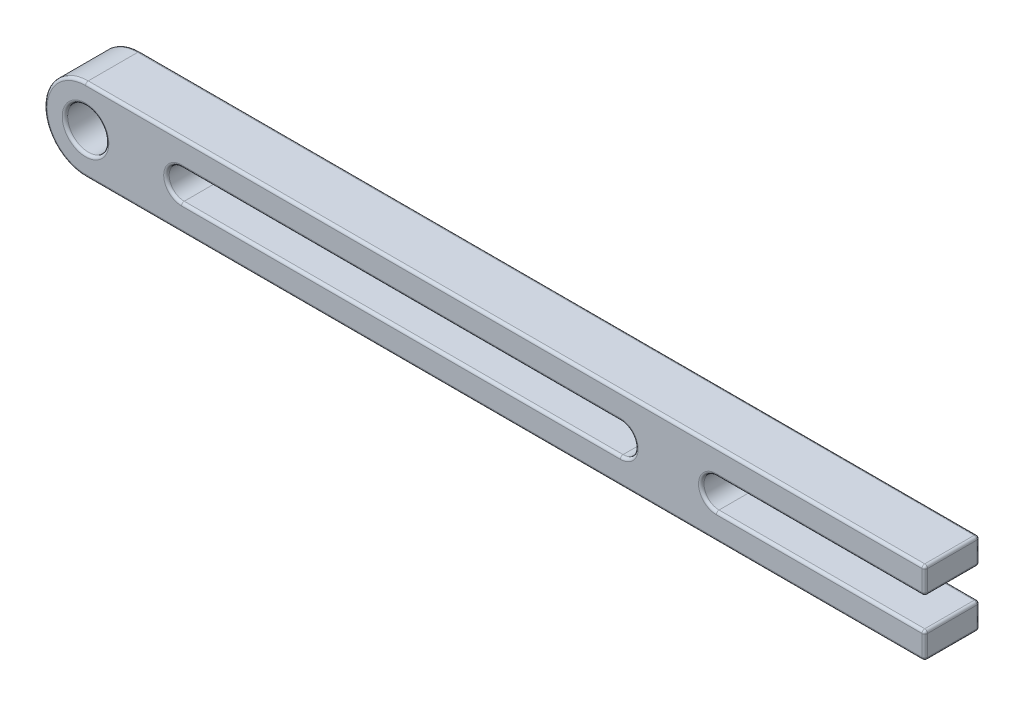
SolidWorks part; units mm, degrees
ref_plane "Front Plane" through (0, 0, 0) normal (0, 0, 1) x (1, 0, 0)
ref_plane "Top Plane" through (0, 0, 0) normal (0, 1, 0) x (1, 0, 0)
ref_plane "Right Plane" through (0, 0, 0) normal (1, 0, 0) x (0, 0, -1)
sketch "Sketch1" plane through (0, 0, 0) normal (0, 0, 1) x (1, 0, 0)
  line L0 (0, -1000) -> (0, 49000) construction
  line L1 (-75, 5.5) -> (85, 5.5)
  line L2 (-75, -5.5) -> (85, -5.5)
  line L3 (-1000, 0) -> (49000, 0) construction
  line L4 (-110, 15) -> (196, 15)
  line L5 (120, 5.5) -> (196, 5.5)
  line L6 (-110, -15) -> (196, -15)
  line L7 (196, 15) -> (196, 5.5)
  line L8 (120, -5.5) -> (196, -5.5)
  line L10 (196, -5.5) -> (196, -15)
  arc A0 (-75, 5.5) -> (-75, -5.5) centre (-75, 0) ccw
  arc A1 (85, -5.5) -> (85, 5.5) centre (85, 0) ccw
  arc A2 (-110, 15) -> (-110, -15) centre (-110, 0) ccw
  circle A3 centre (-110, 0) radius 7.5
  arc A4 (120, 5.5) -> (120, -5.5) centre (120, 0) ccw
  dimension "D5" = 15
  dimension "D1" = 160
  dimension "D2" = 11
  dimension "D3" = 30
  dimension "D4" = 110
  dimension "D6" = 120
  dimension "D7" = 11
  dimension "D8" = 75
  dimension "D9" = 196
extrude "Boss-Extrude1" add sketch "Sketch1" along normal blind 20
fillet "Fillet1" radius 1 30 edges at (158, 5.5, 0) (114.5, 0, 0) (-80.5, 0, 0) (5, 5.5, 0) (90.5, 0, 0) (158, 5.5, 20) (114.5, 0, 20) (-80.5, 0, 20) (5, 5.5, 20) (90.5, 0, 20) (43, -15, 0) (-125, 0, 0) (43, -15, 20) (-125, 0, 20) (196, -15, 10) (196, -10.25, 20) (196, -5.5, 10) (196, -10.25, 0) (196, 5.5, 10) (196, 10.25, 20) (196, 15, 10) (196, 10.25, 0) (158, -5.5, 0) (5, -5.5, 0) (158, -5.5, 20) (5, -5.5, 20) (43, 15, 0) (43, 15, 20) (-102.5, 0, 0) (-102.5, 0, 20)
